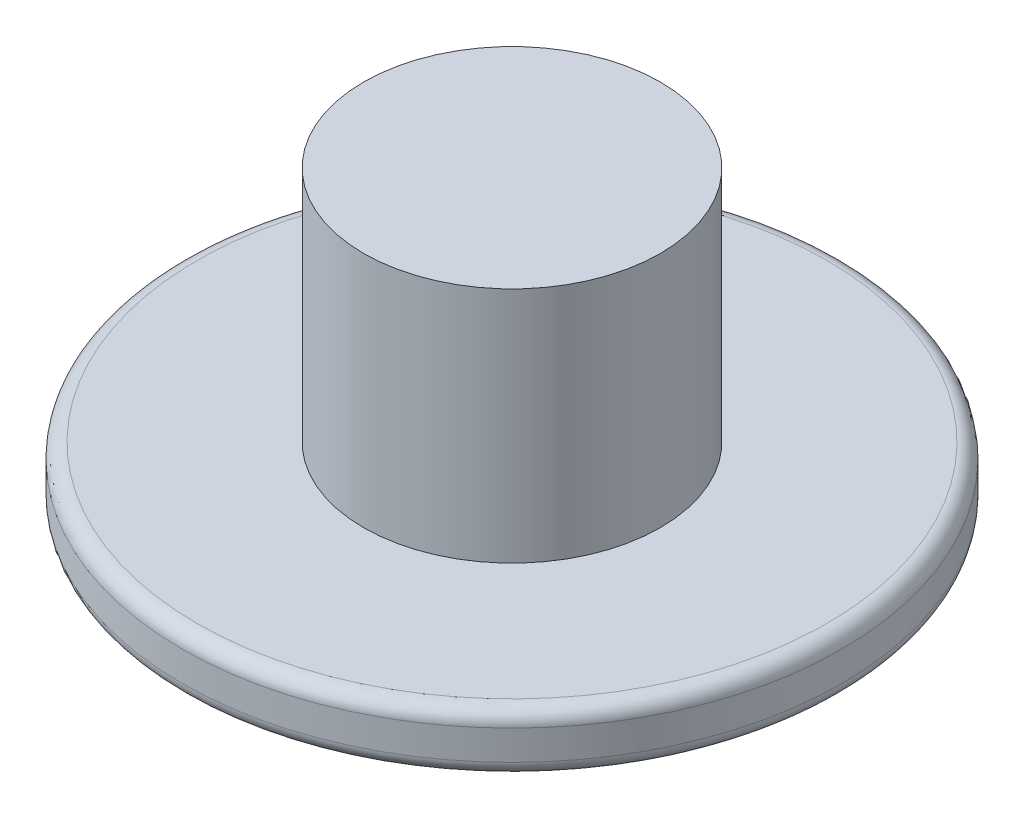
SolidWorks part; units mm, degrees
ref_plane "Front Plane" through (0, 0, 0) normal (0, 0, 1) x (1, 0, 0)
ref_plane "Top Plane" through (0, 0, 0) normal (0, 1, 0) x (1, 0, 0)
ref_plane "Right Plane" through (0, 0, 0) normal (1, 0, 0) x (0, 0, -1)
sketch "Sketch1" plane through (0, 0, 0) normal (0, 1, 0) x (1, 0, 0)
  circle A4 centre (-5.4087, -40.3067) radius 11.1
  circle A12 centre (-5.4087, -40.3067) radius 4.9321
  dimension "D5" = 22.2
extrude "Boss-Extrude5" add sketch "Sketch1" along normal blind 2 contours A4
sketch "Sketch4" plane through (0, 2, 0) normal (0, 1, 0) x (1, 0, 0)
  circle A0 centre (-5.4087, -40.3067) radius 5
  circle A1 centre (-5.4087, -40.3067) radius 11.1 construction
extrude "Boss-Extrude6" add sketch "Sketch4" along normal blind 8
sketch "Sketch5" plane through (0, 0, 0) normal (0, -1, 0) x (1, 0, 0)
  text T0 "50" font "Comic Sans MS" height 10
  point P1 (-5.4087, 25.1919)
  point P2 (0, 0)
  point P3 (-9.5758, 36.1339)
extrude "Cut-Extrude2" cut sketch "Sketch5" against normal blind 0.5
fillet "Fillet1" radius 0.5 2 edges at (-5.4087, 2, 51.4067) (-5.4087, 0, 51.4067)
